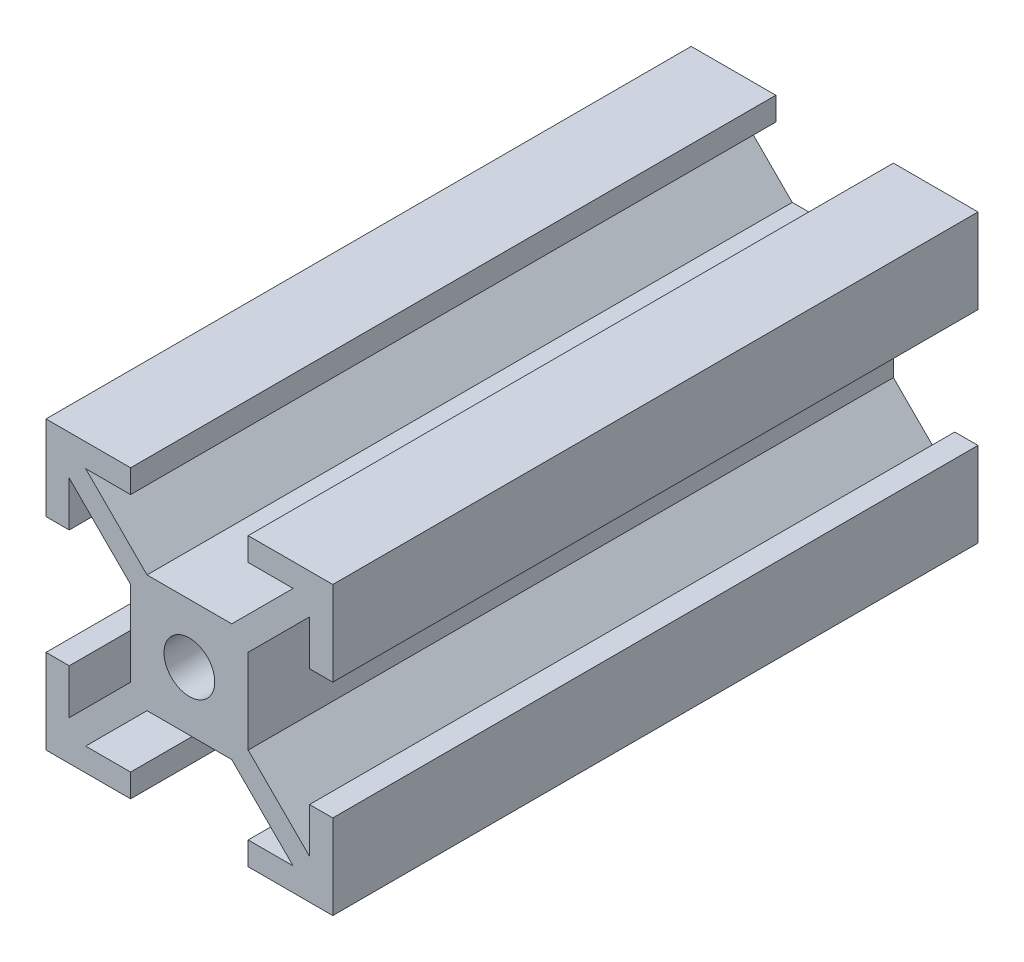
SolidWorks part; units mm, degrees
ref_plane "Front Plane" through (0, 0, 0) normal (0, 0, 1) x (1, 0, 0)
ref_plane "Top Plane" through (0, 0, 0) normal (0, 1, 0) x (1, 0, 0)
ref_plane "Right Plane" through (0, 0, 0) normal (1, 0, 0) x (0, 0, -1)
sketch "Sketch1" plane through (0, 0, 0) normal (0, 0, 1) x (1, 0, 0)
  line L0 (-8.38, 4.1) -> (-10, 4.1)
  line L1 (-2.9545, 4.1) -> (2.9545, 4.1)
  line L2 (-4.1, 2.9545) -> (-4.1, -2.9545)
  line L3 (-2.9545, -4.1) -> (2.9545, -4.1)
  line L4 (4.1, 2.9545) -> (4.1, -2.9545)
  line L5 (-4.1, 4.1) -> (4.1, -4.1) construction
  line L6 (-4.1, -4.1) -> (4.1, 4.1) construction
  line L7 (-10, 10) -> (-4.1, 10)
  line L8 (-10, 10) -> (-10, 4.1)
  line L9 (-10, -10) -> (-4.1, -10)
  line L10 (10, 10) -> (10, 4.1)
  line L11 (-10, 10) -> (10, -10) construction
  line L12 (-10, -10) -> (10, 10) construction
  line L13 (-7.2345, 8.38) -> (-4.1, 8.38)
  line L14 (-8.38, 7.2345) -> (-8.38, 4.1)
  line L15 (-7.2345, -8.38) -> (-4.1, -8.38)
  line L16 (8.38, 7.2345) -> (8.38, 4.1)
  line L17 (-8.38, 8.38) -> (8.38, -8.38) construction
  line L18 (-8.38, -8.38) -> (8.38, 8.38) construction
  line L19 (-4.1, 8.38) -> (-4.1, 10)
  line L20 (4.1, 10) -> (4.1, 8.38)
  line L21 (8.38, 4.1) -> (10, 4.1)
  line L22 (-8.38, -4.1) -> (-10, -4.1)
  line L23 (-4.1, -8.38) -> (-4.1, -10)
  line L24 (8.38, -4.1) -> (10, -4.1)
  line L25 (4.1, -8.38) -> (4.1, -10)
  line L26 (-5.464, 5.464) -> (-4.8912, 6.0368) construction
  line L27 (-4.1, 2.9545) -> (-8.38, 7.2345)
  line L28 (-2.9545, 4.1) -> (-7.2345, 8.38)
  line L29 (0, 11.3108) -> (0, -17.1823) construction
  line L30 (-16.7028, 0) -> (14.4032, 0) construction
  line L31 (-2.9545, -4.1) -> (-7.2345, -8.38)
  line L32 (-4.1, -2.9545) -> (-8.38, -7.2345)
  line L33 (2.9545, -4.1) -> (7.2345, -8.38)
  line L34 (4.1, -2.9545) -> (8.38, -7.2345)
  line L35 (4.1, 2.9545) -> (8.38, 7.2345)
  line L36 (2.9545, 4.1) -> (7.2345, 8.38)
  line L37 (4.1, 8.38) -> (7.2345, 8.38)
  line L38 (4.1, 10) -> (10, 10)
  line L39 (-8.38, -4.1) -> (-8.38, -7.2345)
  line L40 (-10, -4.1) -> (-10, -10)
  line L41 (8.38, -4.1) -> (8.38, -7.2345)
  line L42 (10, -4.1) -> (10, -10)
  line L43 (4.1, -8.38) -> (7.2345, -8.38)
  line L44 (4.1, -10) -> (10, -10)
  circle A0 centre (0, 0) radius 1.77
  point P0 (0, 0)
  point P6 (0, 0)
  dimension "D5" = 3.54
  dimension "D1" = 8.2
  dimension "D2" = 20
  dimension "D3" = 8.2
  dimension "D4" = 20
  dimension "D6" = 16.76
  dimension "D7" = 16.76
  dimension "D8" = 0.81
  dimension "D9" = 135
  dimension "D10" = 7.7696
  dimension "D11" = 5.0536
extrude "Boss-Extrude1" add sketch "Sketch1" along normal blind 45
